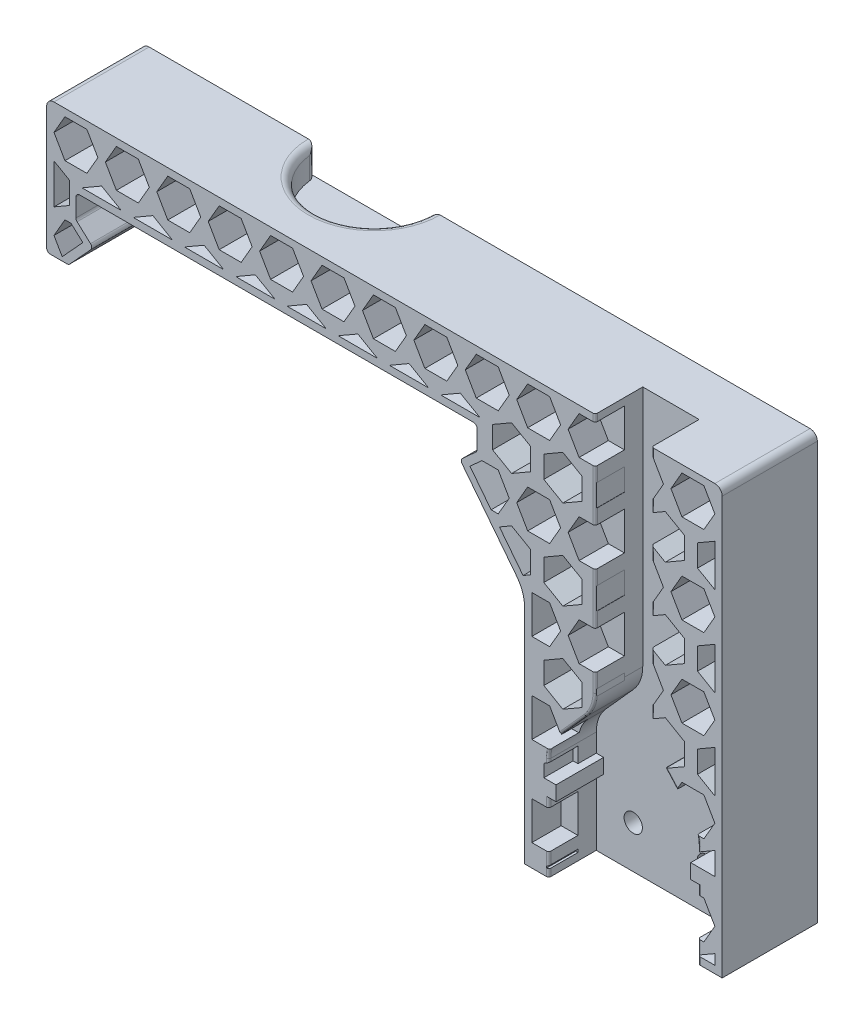
SolidWorks part; units mm, degrees
ref_plane "Front Plane" through (0, 0, 0) normal (0, 0, 1) x (1, 0, 0)
ref_plane "Top Plane" through (0, 0, 0) normal (0, 1, 0) x (1, 0, 0)
ref_plane "Right Plane" through (0, 0, 0) normal (1, 0, 0) x (0, 0, -1)
sketch "Sketch1" plane through (0, 0, 0) normal (0, 0, 1) x (1, 0, 0)
  line L0 (-72.9454, -38.2644) -> (107.2141, -38.2644) construction
  line L1 (-30.4, 19.7356) -> (59.88, 19.7356)
  line L2 (-31.4, 18.7356) -> (-31.4, 1.9656)
  line L3 (33.88, -38.2644) -> (60.88, -38.2644)
  line L4 (60.88, 18.7356) -> (60.88, -38.2644)
  line L5 (25.3801, 4.7612) -> (32.8222, -4.7779)
  line L6 (33.88, -38.2644) -> (33.88, -7.8535)
  line L7 (-66.2153, 1.4656) -> (103.3314, 1.4656) construction
  line L8 (-27.4, 34.7401) -> (-27.4, -56.6339) construction
  line L9 (-30.9, 1.4656) -> (-28.62, 1.4656)
  line L10 (-28.2514, 1.6278) -> (-25.3801, 4.7612)
  line L11 (-25.411, 5.4677) -> (-27.2378, 7.1416)
  line L12 (-40.4336, 7.2903) -> (-15.6218, 7.2903) construction
  line L13 (-40.4336, 10.4903) -> (107.2141, 10.4903) construction
  line L14 (-27.4, 7.5103) -> (-27.4, 9.9903)
  line L15 (0, 58.4136) -> (0, -42.5498) construction
  line L16 (27.4, 7.5103) -> (27.4, 9.9903)
  line L17 (25.411, 5.4677) -> (27.2378, 7.1416)
  line L20 (-26.9, 10.4903) -> (26.9, 10.4903)
  arc A0 (-27.2378, 7.1416) -> (-27.4, 7.5103) centre (-26.9, 7.5103) cw
  arc A1 (-25.3801, 4.7612) -> (-25.411, 5.4677) centre (-25.7488, 5.099) ccw
  arc A2 (-28.2514, 1.6278) -> (-28.62, 1.4656) centre (-28.62, 1.9656) cw
  arc A3 (-30.9, 1.4656) -> (-31.4, 1.9656) centre (-30.9, 1.9656) cw
  arc A4 (27.2378, 7.1416) -> (27.4, 7.5103) centre (26.9, 7.5103) ccw
  arc A5 (25.3801, 4.7612) -> (25.411, 5.4677) centre (25.7488, 5.099) cw
  arc A6 (33.88, -7.8535) -> (32.8222, -4.7779) centre (28.88, -7.8535) ccw
  arc A7 (-30.4, 19.7356) -> (-31.4, 18.7356) centre (-30.4, 18.7356) ccw
  arc A8 (27.4, 9.9903) -> (26.9, 10.4903) centre (26.9, 9.9903) ccw
  arc A9 (-26.9, 10.4903) -> (-27.4, 9.9903) centre (-26.9, 9.9903) ccw
  arc A10 (60.88, 18.7356) -> (59.88, 19.7356) centre (59.88, 18.7356) ccw
  point P0 (0, 0)
  point P23 (-27.4, 7.2903)
  point P26 (-25.0423, 5.1299)
  point P29 (-28.4, 1.4656)
  point P49 (27.4, 10.4903)
  point P52 (-27.4, 10.4903)
  point P53 (-31.4, 19.7356)
  point P56 (60.88, 19.7356)
  dimension "D11" = 0.5
  dimension "D12" = 0.5
  dimension "D15" = 5
  dimension "D16" = 1
  dimension "D1" = 92.28
  dimension "D2" = 58
  dimension "D3" = 18.27
  dimension "D4" = 4
  dimension "D5" = 132.5
  dimension "D6" = 4.97
  dimension "D7" = 90
  dimension "D8" = 54.8
  dimension "D9" = 3.1978
  dimension "D10" = 3.2
  dimension "D13" = 27
  dimension "D14" = 142.04
extrude "Boss-Extrude1" add sketch "Sketch1" along normal mid plane 13
sketch "Sketch2" plane through (0, 19.7356, 0) normal (0, 1, 0) x (1, 0, 0)
  line L0 (0.35, 16.9298) -> (0.35, -17.4429) construction
  line L1 (-31.4, -6.5) -> (-31.4, 6.5) construction
  circle A0 centre (0.35, 6.5) radius 8
  dimension "D2" = 16
  dimension "D1" = 31.75
extrude "Cut-Extrude1" cut sketch "Sketch2" against normal blind 4
fillet "Fillet1" radius 1 3 edges at (-7.65, 17.7356, -6.5) (8.35, 17.7356, -6.5) (0.35, 19.7356, 1.5)
sketch "Sketch3" plane through (0, 0, 6.5) normal (0, 0, 1) x (1, 0, 0)
  line L0 (47.38, -46.7699) -> (47.38, 28.5423) construction
  line L1 (0, -32.4644) -> (121.6508, -32.4644) construction
  line L2 (0, -28.7644) -> (121.6508, -28.7644) construction
  line L3 (33.88, -7.8535) -> (33.88, -38.2644) construction
  line L4 (60.88, -38.2644) -> (60.88, 18.7356) construction
  line L5 (43.53, 19.7356) -> (43.53, -13.3516)
  line L6 (59.88, 19.7356) -> (-30.4, 19.7356) construction
  line L7 (51.23, 19.7356) -> (51.23, -13.3516)
  line L8 (37.18, -38.2644) -> (37.18, -24.2619)
  line L9 (33.88, -38.2644) -> (60.88, -38.2644) construction
  line L10 (57.58, -38.2644) -> (57.58, -24.2619)
  line L11 (52.5067, -16.6888) -> (56.3033, -20.9247)
  line L12 (42.2533, -16.6888) -> (38.4567, -20.9247)
  line L13 (53.48, -29.3335) -> (53.48, -36.8232) construction
  line L14 (50.98, -29.3335) -> (50.98, -36.8232) construction
  line L15 (43.48, -29.3335) -> (43.48, -36.8232) construction
  line L16 (37.18, -26.7644) -> (38.18, -26.7644)
  line L17 (57.58, -28.7644) -> (56.58, -28.7644)
  line L19 (57.58, -26.7644) -> (56.58, -26.7644)
  line L20 (56.58, -28.7644) -> (56.58, -26.7644)
  line L21 (38.18, -28.7644) -> (38.18, -26.7644)
  line L22 (37.18, -28.7644) -> (38.18, -28.7644)
  line L24 (37.18, -38.2644) -> (57.58, -38.2644)
  line L25 (43.53, 19.7356) -> (51.23, 19.7356)
  arc A0 (42.2533, -16.6888) -> (43.53, -13.3516) centre (38.53, -13.3516) ccw
  arc A1 (52.5067, -16.6888) -> (51.23, -13.3516) centre (56.23, -13.3516) cw
  arc A2 (57.58, -24.2619) -> (56.3033, -20.9247) centre (52.58, -24.2619) ccw
  arc A3 (37.18, -24.2619) -> (38.4567, -20.9247) centre (42.18, -24.2619) cw
  circle A4 centre (52.23, -32.4644) radius 1.25
  circle A5 centre (42.23, -32.4644) radius 1.25
  point P27 (51.23, -15.2644)
  line M20 (59.88, 19.7356) -> (-30.4, 19.7356)
  line M41 (33.88, -38.2644) -> (60.88, -38.2644)
  dimension "D6" = 5
  dimension "D7" = 5
  dimension "D10" = 2.5
  dimension "D12" = 2.5
  dimension "D1" = 7.7
  dimension "D2" = 35
  dimension "D3" = 138.13
  dimension "D4" = 138.13
  dimension "D5" = 20.4
  dimension "D8" = 5.8
  dimension "D9" = 9.5
  dimension "D11" = 4.1
  dimension "D13" = 7.5
  dimension "D14" = 1
  dimension "D15" = 2
extrude "Cut-Extrude2" cut sketch "Sketch3" against normal blind 6.5 contours A3 L8 L16 L21 L22 L10 L17 L20 L19 A2 L11 A1 L7 L5 A0 L12 A5 A4 M41 M20
sketch "Sketch4" plane through (0, 0, 6.5) normal (0, 0, 1) x (1, 0, 0)
  circle A0 centre (42.23, -32.4644) radius 1.25
  circle A1 centre (52.23, -32.4644) radius 1.25
extrude "Cut-Extrude3" cut sketch "Sketch4" against normal blind 10
fillet "Fillet2" radius 0.3 12 edges at (51.23, 3.192, 6.5) (51.5601, -15.1381, 6.5) (57.58, -25.5131, 6.5) (57.2499, -22.4753, 6.5) (37.18, -25.5131, 6.5) (37.5101, -22.4753, 6.5) (40.355, -18.8067, 6.5) (43.1999, -15.1381, 6.5) (37.18, -33.5144, 6.5) (57.58, -33.5144, 6.5) (54.405, -18.8067, 6.5) (43.53, 3.192, 6.5)
sketch "Sketch5" plane through (0, 0, 6.5) normal (0, 0, 1) x (1, 0, 0)
  line L0 (-31.4, 18.7356) -> (-31.4, 1.9656) construction
  line L1 (-25.9, 13.5394) -> (-24.4, 16.1375)
  line L2 (-24.4, 16.1375) -> (-25.9, 18.7356)
  line L3 (-25.9, 18.7356) -> (-28.9, 18.7356)
  line L4 (-28.9, 18.7356) -> (-30.4, 16.1375)
  line L5 (-30.4, 16.1375) -> (-28.9, 13.5394)
  line L6 (-28.9, 13.5394) -> (-25.9, 13.5394)
  line L7 (43.23, 19.7356) -> (-30.4, 19.7356) construction
  line L8 (-18.8767, 13.5394) -> (-17.3767, 16.1375)
  line L9 (-17.3767, 16.1375) -> (-18.8767, 18.7356)
  line L10 (-18.8767, 18.7356) -> (-21.8767, 18.7356)
  line L11 (-21.8767, 18.7356) -> (-23.3767, 16.1375)
  line L12 (-23.3767, 16.1375) -> (-21.8767, 13.5394)
  line L13 (-21.8767, 13.5394) -> (-18.8767, 13.5394)
  line L14 (-11.8533, 13.5394) -> (-10.3533, 16.1375)
  line L15 (-10.3533, 16.1375) -> (-11.8533, 18.7356)
  line L16 (-11.8533, 18.7356) -> (-14.8533, 18.7356)
  line L17 (-14.8533, 18.7356) -> (-16.3533, 16.1375)
  line L18 (-16.3533, 16.1375) -> (-14.8533, 13.5394)
  line L19 (-14.8533, 13.5394) -> (-11.8533, 13.5394)
  line L20 (-4.83, 13.5394) -> (-3.33, 16.1375)
  line L21 (-3.33, 16.1375) -> (-4.83, 18.7356)
  line L22 (-4.83, 18.7356) -> (-7.83, 18.7356)
  line L23 (-7.83, 18.7356) -> (-9.33, 16.1375)
  line L24 (-9.33, 16.1375) -> (-7.83, 13.5394)
  line L25 (-7.83, 13.5394) -> (-4.83, 13.5394)
  line L26 (2.1933, 13.5394) -> (3.6933, 16.1375)
  line L27 (3.6933, 16.1375) -> (2.1933, 18.7356)
  line L28 (2.1933, 18.7356) -> (-0.8067, 18.7356)
  line L29 (-0.8067, 18.7356) -> (-2.3067, 16.1375)
  line L30 (-2.3067, 16.1375) -> (-0.8067, 13.5394)
  line L31 (-0.8067, 13.5394) -> (2.1933, 13.5394)
  line L32 (9.2167, 13.5394) -> (10.7167, 16.1375)
  line L33 (10.7167, 16.1375) -> (9.2167, 18.7356)
  line L34 (9.2167, 18.7356) -> (6.2167, 18.7356)
  line L35 (6.2167, 18.7356) -> (4.7167, 16.1375)
  line L36 (4.7167, 16.1375) -> (6.2167, 13.5394)
  line L37 (6.2167, 13.5394) -> (9.2167, 13.5394)
  line L38 (16.24, 13.5394) -> (17.74, 16.1375)
  line L39 (17.74, 16.1375) -> (16.24, 18.7356)
  line L40 (16.24, 18.7356) -> (13.24, 18.7356)
  line L41 (13.24, 18.7356) -> (11.74, 16.1375)
  line L42 (11.74, 16.1375) -> (13.24, 13.5394)
  line L43 (13.24, 13.5394) -> (16.24, 13.5394)
  line L44 (23.2633, 13.5394) -> (24.7633, 16.1375)
  line L45 (24.7633, 16.1375) -> (23.2633, 18.7356)
  line L46 (23.2633, 18.7356) -> (20.2633, 18.7356)
  line L47 (20.2633, 18.7356) -> (18.7633, 16.1375)
  line L48 (18.7633, 16.1375) -> (20.2633, 13.5394)
  line L49 (20.2633, 13.5394) -> (23.2633, 13.5394)
  line L50 (30.2867, 13.5394) -> (31.7867, 16.1375)
  line L51 (31.7867, 16.1375) -> (30.2867, 18.7356)
  line L52 (30.2867, 18.7356) -> (27.2867, 18.7356)
  line L53 (27.2867, 18.7356) -> (25.7867, 16.1375)
  line L54 (25.7867, 16.1375) -> (27.2867, 13.5394)
  line L55 (27.2867, 13.5394) -> (30.2867, 13.5394)
  line L56 (37.31, 13.5394) -> (38.81, 16.1375)
  line L57 (38.81, 16.1375) -> (37.31, 18.7356)
  line L58 (37.31, 18.7356) -> (34.31, 18.7356)
  line L59 (34.31, 18.7356) -> (32.81, 16.1375)
  line L60 (32.81, 16.1375) -> (34.31, 13.5394)
  line L61 (34.31, 13.5394) -> (37.31, 13.5394)
  line L62 (44.3333, 13.5394) -> (45.8333, 16.1375)
  line L63 (45.8333, 16.1375) -> (44.3333, 18.7356)
  line L64 (44.3333, 18.7356) -> (41.3333, 18.7356)
  line L65 (41.3333, 18.7356) -> (39.8333, 16.1375)
  line L66 (39.8333, 16.1375) -> (41.3333, 13.5394)
  line L67 (41.3333, 13.5394) -> (44.3333, 13.5394)
  line L68 (51.3567, 13.5394) -> (52.8567, 16.1375)
  line L69 (52.8567, 16.1375) -> (51.3567, 18.7356)
  line L70 (51.3567, 18.7356) -> (48.3567, 18.7356)
  line L71 (48.3567, 18.7356) -> (46.8567, 16.1375)
  line L72 (46.8567, 16.1375) -> (48.3567, 13.5394)
  line L73 (48.3567, 13.5394) -> (51.3567, 13.5394)
  line L74 (58.38, 13.5394) -> (59.88, 16.1375)
  line L75 (59.88, 16.1375) -> (58.38, 18.7356)
  line L76 (58.38, 18.7356) -> (55.38, 18.7356)
  line L77 (55.38, 18.7356) -> (53.88, 16.1375)
  line L78 (53.88, 16.1375) -> (55.38, 13.5394)
  line L79 (55.38, 13.5394) -> (58.38, 13.5394)
  line L80 (60.88, -38.2644) -> (60.88, 18.7356) construction
  line L81 (-23.8883, 20.8611) -> (-23.8883, 11.4903) construction
  line L89 (-21.2903, 11.4903) -> (-21.2903, 11.5394)
  line L90 (-21.2903, 11.5394) -> (-23.8883, 13.0394)
  line L91 (-23.8883, 13.0394) -> (-26.4864, 11.5394)
  line L92 (-26.4864, 11.5394) -> (-26.4864, 11.4903)
  line L95 (-14.2903, 11.4903) -> (-14.2903, 11.5394)
  line L96 (-14.2903, 11.5394) -> (-16.8883, 13.0394)
  line L97 (-16.8883, 13.0394) -> (-19.4864, 11.5394)
  line L98 (-19.4864, 11.5394) -> (-19.4864, 11.4903)
  line L101 (-7.2903, 11.4903) -> (-7.2903, 11.5394)
  line L102 (-7.2903, 11.5394) -> (-9.8883, 13.0394)
  line L103 (-9.8883, 13.0394) -> (-12.4864, 11.5394)
  line L104 (-12.4864, 11.5394) -> (-12.4864, 11.4903)
  line L107 (-0.2903, 11.4903) -> (-0.2903, 11.5394)
  line L108 (-0.2903, 11.5394) -> (-2.8883, 13.0394)
  line L109 (-2.8883, 13.0394) -> (-5.4864, 11.5394)
  line L110 (-5.4864, 11.5394) -> (-5.4864, 11.4903)
  line L113 (6.7097, 11.4903) -> (6.7097, 11.5394)
  line L114 (6.7097, 11.5394) -> (4.1117, 13.0394)
  line L115 (4.1117, 13.0394) -> (1.5136, 11.5394)
  line L116 (1.5136, 11.5394) -> (1.5136, 11.4903)
  line L119 (13.7097, 11.4903) -> (13.7097, 11.5394)
  line L120 (13.7097, 11.5394) -> (11.1117, 13.0394)
  line L121 (11.1117, 13.0394) -> (8.5136, 11.5394)
  line L122 (8.5136, 11.5394) -> (8.5136, 11.4903)
  line L125 (20.7097, 11.4903) -> (20.7097, 11.5394)
  line L126 (20.7097, 11.5394) -> (18.1117, 13.0394)
  line L127 (18.1117, 13.0394) -> (15.5136, 11.5394)
  line L128 (15.5136, 11.5394) -> (15.5136, 11.4903)
  line L131 (27.7097, 11.4903) -> (27.7097, 11.5394)
  line L132 (27.7097, 11.5394) -> (25.1117, 13.0394)
  line L133 (25.1117, 13.0394) -> (22.5136, 11.5394)
  line L134 (22.5136, 11.5394) -> (22.5136, 11.4903)
  line L142 (39.1117, 7.0394) -> (41.7097, 8.5394)
  line L143 (41.7097, 8.5394) -> (41.7097, 11.5394)
  line L144 (41.7097, 11.5394) -> (39.1117, 13.0394)
  line L145 (39.1117, 13.0394) -> (36.5136, 11.5394)
  line L146 (36.5136, 11.5394) -> (36.5136, 8.5394)
  line L147 (36.5136, 8.5394) -> (39.1117, 7.0394)
  line L148 (46.1117, 7.0394) -> (48.7097, 8.5394)
  line L149 (48.7097, 8.5394) -> (48.7097, 11.5394)
  line L150 (48.7097, 11.5394) -> (46.1117, 13.0394)
  line L151 (46.1117, 13.0394) -> (43.5136, 11.5394)
  line L152 (43.5136, 11.5394) -> (43.5136, 8.5394)
  line L153 (43.5136, 8.5394) -> (46.1117, 7.0394)
  line L154 (53.1117, 7.0394) -> (55.7097, 8.5394)
  line L155 (55.7097, 8.5394) -> (55.7097, 11.5394)
  line L156 (55.7097, 11.5394) -> (53.1117, 13.0394)
  line L157 (53.1117, 13.0394) -> (50.5136, 11.5394)
  line L158 (50.5136, 11.5394) -> (50.5136, 8.5394)
  line L159 (50.5136, 8.5394) -> (53.1117, 7.0394)
  line L163 (59.88, 12.9057) -> (57.5136, 11.5394)
  line L164 (57.5136, 11.5394) -> (57.5136, 8.5394)
  line L165 (57.5136, 8.5394) -> (59.88, 7.1732)
  line L166 (-30.4, 7.3214) -> (-28.2903, 8.5394)
  line L167 (-28.2903, 8.5394) -> (-28.2903, 11.5394)
  line L168 (-28.2903, 11.5394) -> (-30.4, 12.7575)
  line L172 (-30.4, 25.6172) -> (-30.4, -2.2166) construction
  line L173 (59.88, 25.6172) -> (59.88, -37.2644) construction
  line L174 (34.88, -39.7832) -> (34.88, 44.6202) construction
  line L175 (33.88, -7.8535) -> (33.88, -38.2644) construction
  line L176 (-30.4, 12.7575) -> (-30.4, 7.3214)
  line L177 (-27.5969, 11.4903) -> (59.88, 11.4903) construction
  line L178 (-26.9, 10.4903) -> (26.9, 10.4903) construction
  line L179 (-30.8883, 13.0394) -> (-33.4864, 11.5394) [skipped]
  line L180 (-33.4864, 11.5394) -> (-33.4864, 8.5394) [skipped]
  line L181 (32.1117, 7.0394) -> (34.7097, 8.5394)
  line L182 (-26.4864, 11.4903) -> (-21.2903, 11.4903)
  line L183 (-19.4864, 11.4903) -> (-14.2903, 11.4903)
  line L184 (-12.4864, 11.4903) -> (-7.2903, 11.4903)
  line L185 (-5.4864, 11.4903) -> (-0.2903, 11.4903)
  line L186 (1.5136, 11.4903) -> (6.7097, 11.4903)
  line L187 (8.5136, 11.4903) -> (13.7097, 11.4903)
  line L188 (15.5136, 11.4903) -> (20.7097, 11.4903)
  line L189 (22.5136, 11.4903) -> (27.7097, 11.4903)
  line L190 (59.88, 12.9057) -> (59.88, 7.1732)
  line L191 (-23.8883, 7.4414) -> (-23.8883, 3.5852) construction
  line L192 (34.7097, 8.5394) -> (34.7097, 11.5394)
  line L193 (62.7097, 11.5394) -> (60.1117, 13.0394) [skipped]
  line L194 (34.7097, 11.5394) -> (32.1117, 13.0394)
  line L195 (62.7097, 11.4903) -> (62.7097, 11.5394) [skipped]
  line L196 (32.1117, 13.0394) -> (29.5136, 11.5394)
  line L197 (29.5136, 11.5394) -> (29.5136, 8.5394)
  line L198 (29.5136, 8.5394) -> (32.1117, 7.0394)
  line L199 (-34.5969, 11.4903) -> (52.88, 11.4903) construction
  line L200 (-25.1874, 7.7894) -> (-23.8883, 7.0394) [skipped]
  line L201 (-23.8883, 7.0394) -> (-21.2903, 8.5394) [skipped]
  line L202 (29.5136, 11.5394) -> (29.5136, 11.4903) [skipped]
  line L203 (32.1117, 13.0394) -> (29.5136, 11.5394) [skipped]
  line L204 (34.7097, 11.4903) -> (34.7097, 11.5394) [skipped]
  line L205 (34.7097, 11.5394) -> (32.1117, 13.0394) [skipped]
  line L208 (-28.0608, 6.5394) -> (-28.9, 6.5394)
  line L209 (-28.9, 6.5394) -> (-30.4, 3.9414)
  line L210 (-30.4, 3.9414) -> (-29.2743, 1.9916)
  line L254 (30.2867, 1.3433) -> (31.7867, 3.9414)
  line L255 (31.7867, 3.9414) -> (30.2867, 6.5394)
  line L256 (30.2867, 6.5394) -> (28.0608, 6.5394)
  line L257 (26.4252, 5.0473) -> (26.4171, 5.0332)
  line L259 (29.315, 1.3433) -> (30.2867, 1.3433)
  line L260 (37.31, 1.3433) -> (38.81, 3.9414)
  line L261 (38.81, 3.9414) -> (37.31, 6.5394)
  line L262 (37.31, 6.5394) -> (34.31, 6.5394)
  line L263 (34.31, 6.5394) -> (32.81, 3.9414)
  line L264 (32.81, 3.9414) -> (34.31, 1.3433)
  line L265 (34.31, 1.3433) -> (37.31, 1.3433)
  line L266 (44.3333, 1.3433) -> (45.8333, 3.9414)
  line L267 (45.8333, 3.9414) -> (44.3333, 6.5394)
  line L268 (44.3333, 6.5394) -> (41.3333, 6.5394)
  line L269 (41.3333, 6.5394) -> (39.8333, 3.9414)
  line L270 (39.8333, 3.9414) -> (41.3333, 1.3433)
  line L271 (41.3333, 1.3433) -> (44.3333, 1.3433)
  line L272 (51.3567, 1.3433) -> (52.8567, 3.9414)
  line L273 (52.8567, 3.9414) -> (51.3567, 6.5394)
  line L274 (51.3567, 6.5394) -> (48.3567, 6.5394)
  line L275 (48.3567, 6.5394) -> (46.8567, 3.9414)
  line L276 (46.8567, 3.9414) -> (48.3567, 1.3433)
  line L277 (48.3567, 1.3433) -> (51.3567, 1.3433)
  line L278 (58.38, 1.3433) -> (59.88, 3.9414)
  line L279 (59.88, 3.9414) -> (58.38, 6.5394)
  line L280 (58.38, 6.5394) -> (55.38, 6.5394)
  line L281 (55.38, 6.5394) -> (53.88, 3.9414)
  line L282 (53.88, 3.9414) -> (55.38, 1.3433)
  line L283 (55.38, 1.3433) -> (58.38, 1.3433)
  line L284 (-29.9967, 1.2033) -> (-24.7531, 6.9257) construction
  line L285 (-28.2514, 1.6278) -> (-25.3801, 4.7612) construction
  line L286 (-23.2608, 2.1411) -> (-28.8272, 7.2417) construction
  line L287 (-25.411, 5.4677) -> (-27.2378, 7.1416) construction
  line L288 (-28.0608, 6.5394) -> (-26.4552, 5.0682)
  line L289 (-26.4552, 5.0682) -> (-29.2743, 1.9916)
  line L290 (36.4614, -7.8169) -> (25.0514, 6.8083) construction
  line L291 (25.3801, 4.7612) -> (32.8222, -4.7779) construction
  line L292 (-28.9, 1.3433) -> (-25.9, 1.3433) [skipped]
  line L293 (-24.6856, 3.4467) -> (-24.4, 3.9414) [skipped]
  line L294 (-25.5935, 6.0085) -> (-25.9, 6.5394) [skipped]
  line L295 (-21.8767, 1.3433) -> (-18.8767, 1.3433) [skipped]
  line L296 (-23.3767, 3.9414) -> (-21.8767, 1.3433) [skipped]
  line L297 (-21.8767, 6.5394) -> (-23.3767, 3.9414) [skipped]
  line L298 (-18.8767, 6.5394) -> (-21.8767, 6.5394) [skipped]
  line L299 (-17.3767, 3.9414) -> (-18.8767, 6.5394) [skipped]
  line L300 (-18.8767, 1.3433) -> (-17.3767, 3.9414) [skipped]
  line L301 (-11.8533, 1.3433) -> (-10.3533, 3.9414) [skipped]
  line L302 (-14.8533, 1.3433) -> (-11.8533, 1.3433) [skipped]
  line L303 (-10.3533, 3.9414) -> (-11.8533, 6.5394) [skipped]
  line L304 (-14.8533, 6.5394) -> (-16.3533, 3.9414) [skipped]
  line L305 (-11.8533, 6.5394) -> (-14.8533, 6.5394) [skipped]
  line L306 (-16.3533, 3.9414) -> (-14.8533, 1.3433) [skipped]
  line L307 (-7.83, 1.3433) -> (-4.83, 1.3433) [skipped]
  line L308 (-4.83, 1.3433) -> (-3.33, 3.9414) [skipped]
  line L309 (-3.33, 3.9414) -> (-4.83, 6.5394) [skipped]
  line L310 (-4.83, 6.5394) -> (-7.83, 6.5394) [skipped]
  line L311 (-7.83, 6.5394) -> (-9.33, 3.9414) [skipped]
  line L312 (-9.33, 3.9414) -> (-7.83, 1.3433) [skipped]
  line L313 (20.2633, 1.3433) -> (23.2633, 1.3433) [skipped]
  line L314 (23.2633, 6.5394) -> (20.2633, 6.5394) [skipped]
  line L315 (20.2633, 6.5394) -> (18.7633, 3.9414) [skipped]
  line L316 (18.7633, 3.9414) -> (20.2633, 1.3433) [skipped]
  line L317 (16.24, 1.3433) -> (17.74, 3.9414) [skipped]
  line L318 (13.24, 1.3433) -> (16.24, 1.3433) [skipped]
  line L319 (11.74, 3.9414) -> (13.24, 1.3433) [skipped]
  line L320 (13.24, 6.5394) -> (11.74, 3.9414) [skipped]
  line L321 (16.24, 6.5394) -> (13.24, 6.5394) [skipped]
  line L322 (17.74, 3.9414) -> (16.24, 6.5394) [skipped]
  line L323 (9.2167, 1.3433) -> (10.7167, 3.9414) [skipped]
  line L324 (10.7167, 3.9414) -> (9.2167, 6.5394) [skipped]
  line L325 (4.7167, 3.9414) -> (6.2167, 1.3433) [skipped]
  line L326 (6.2167, 1.3433) -> (9.2167, 1.3433) [skipped]
  line L327 (6.2167, 6.5394) -> (4.7167, 3.9414) [skipped]
  line L328 (9.2167, 6.5394) -> (6.2167, 6.5394) [skipped]
  line L329 (2.1933, 1.3433) -> (3.6933, 3.9414) [skipped]
  line L330 (-0.8067, 1.3433) -> (2.1933, 1.3433) [skipped]
  line L331 (-2.3067, 3.9414) -> (-0.8067, 1.3433) [skipped]
  line L332 (-0.8067, 6.5394) -> (-2.3067, 3.9414) [skipped]
  line L333 (2.1933, 6.5394) -> (-0.8067, 6.5394) [skipped]
  line L334 (3.6933, 3.9414) -> (2.1933, 6.5394) [skipped]
  line L335 (23.2633, 1.3433) -> (24.7633, 3.9414) [skipped]
  line L336 (24.7633, 3.9414) -> (23.2633, 6.5394) [skipped]
  line L337 (26.4171, 5.0332) -> (28.9645, 7.3675) construction
  line L338 (27.2378, 7.1416) -> (25.411, 5.4677) construction
  line L339 (29.315, 1.3433) -> (26.4252, 5.0473)
  line L340 (26.4252, 5.0473) -> (28.0608, 6.5394)
  line L341 (33.6797, -4.2514) -> (34.7097, -3.6567)
  line L342 (34.7097, -3.6567) -> (34.7097, -0.6567)
  line L343 (25.7867, 3.9414) -> (27.2867, 1.3433) [skipped]
  line L344 (34.7097, -0.6567) -> (32.1117, 0.8433)
  line L345 (32.1117, 0.8433) -> (30.4524, -0.1147)
  line L348 (46.1117, -5.1567) -> (48.7097, -3.6567)
  line L349 (48.7097, -3.6567) -> (48.7097, -0.6567)
  line L350 (48.7097, -0.6567) -> (46.1117, 0.8433)
  line L351 (46.1117, 0.8433) -> (43.5136, -0.6567)
  line L352 (43.5136, -0.6567) -> (43.5136, -3.6567)
  line L353 (43.5136, -3.6567) -> (46.1117, -5.1567)
  line L354 (53.1117, -5.1567) -> (55.7097, -3.6567)
  line L355 (55.7097, -3.6567) -> (55.7097, -0.6567)
  line L356 (55.7097, -0.6567) -> (53.1117, 0.8433)
  line L357 (53.1117, 0.8433) -> (50.5136, -0.6567)
  line L358 (50.5136, -0.6567) -> (50.5136, -3.6567)
  line L359 (50.5136, -3.6567) -> (53.1117, -5.1567)
  line L360 (57.5136, -0.6567) -> (57.5136, -3.6567)
  line L361 (57.5136, -3.6567) -> (59.88, -5.023)
  line L362 (59.88, 0.7095) -> (59.88, -5.023)
  line L363 (59.88, 0.7095) -> (57.5136, -0.6567)
  line L364 (39.1117, -5.1567) -> (41.7097, -3.6567)
  line L365 (41.7097, -3.6567) -> (41.7097, -0.6567)
  line L366 (41.7097, -0.6567) -> (39.1117, 0.8433)
  line L367 (39.1117, 0.8433) -> (36.5136, -0.6567)
  line L368 (36.5136, -0.6567) -> (36.5136, -3.6567)
  line L369 (36.5136, -3.6567) -> (39.1117, -5.1567)
  line L370 (43.23, -13.3516) -> (43.23, 19.7356) construction
  line L371 (30.4524, -0.1147) -> (33.6797, -4.2514)
  line L372 (37.31, -10.8529) -> (38.81, -8.2548)
  line L373 (38.81, -8.2548) -> (37.31, -5.6567)
  line L374 (29.5136, -0.6567) -> (29.5136, -3.6567) [skipped]
  line L375 (29.5136, -3.6567) -> (32.1117, -5.1567) [skipped]
  line L376 (37.31, -5.6567) -> (34.88, -5.6567)
  line L379 (34.88, -10.8529) -> (37.31, -10.8529)
  line L380 (44.3333, -10.8529) -> (45.8333, -8.2548)
  line L381 (45.8333, -8.2548) -> (44.3333, -5.6567)
  line L382 (44.3333, -5.6567) -> (41.3333, -5.6567)
  line L383 (41.3333, -5.6567) -> (39.8333, -8.2548)
  line L384 (39.8333, -8.2548) -> (41.3333, -10.8529)
  line L385 (41.3333, -10.8529) -> (44.3333, -10.8529)
  line L386 (51.3567, -10.8529) -> (52.8567, -8.2548)
  line L387 (52.8567, -8.2548) -> (51.3567, -5.6567)
  line L388 (51.3567, -5.6567) -> (48.3567, -5.6567)
  line L389 (48.3567, -5.6567) -> (46.8567, -8.2548)
  line L390 (46.8567, -8.2548) -> (48.3567, -10.8529)
  line L391 (48.3567, -10.8529) -> (51.3567, -10.8529)
  line L392 (58.38, -10.8529) -> (59.88, -8.2548)
  line L393 (59.88, -8.2548) -> (58.38, -5.6567)
  line L394 (58.38, -5.6567) -> (55.38, -5.6567)
  line L395 (55.38, -5.6567) -> (53.88, -8.2548)
  line L396 (53.88, -8.2548) -> (55.38, -10.8529)
  line L397 (55.38, -10.8529) -> (58.38, -10.8529)
  line L398 (34.88, -5.6567) -> (34.88, -10.8529)
  line L401 (32.81, -8.2548) -> (34.31, -10.8529) [skipped]
  line L402 (34.31, -5.6567) -> (32.81, -8.2548) [skipped]
  line L407 (39.1117, -17.3529) -> (41.7097, -15.8529)
  line L408 (41.7097, -15.8529) -> (41.7097, -12.8529)
  line L409 (41.7097, -12.8529) -> (39.1117, -11.3529)
  line L410 (39.1117, -11.3529) -> (36.5136, -12.8529)
  line L411 (36.5136, -12.8529) -> (36.5136, -15.8529)
  line L412 (36.5136, -15.8529) -> (39.1117, -17.3529)
  line L413 (46.1117, -17.3529) -> (48.7097, -15.8529)
  line L414 (48.7097, -15.8529) -> (48.7097, -12.8529)
  line L415 (48.7097, -12.8529) -> (46.1117, -11.3529)
  line L416 (46.1117, -11.3529) -> (43.5136, -12.8529)
  line L417 (43.5136, -12.8529) -> (43.5136, -15.8529)
  line L418 (43.5136, -15.8529) -> (46.1117, -17.3529)
  line L419 (53.1117, -17.3529) -> (55.7097, -15.8529)
  line L420 (55.7097, -15.8529) -> (55.7097, -12.8529)
  line L421 (55.7097, -12.8529) -> (53.1117, -11.3529)
  line L422 (53.1117, -11.3529) -> (50.5136, -12.8529)
  line L423 (50.5136, -12.8529) -> (50.5136, -15.8529)
  line L424 (50.5136, -15.8529) -> (53.1117, -17.3529)
  line L425 (57.5136, -12.8529) -> (57.5136, -15.8529)
  line L426 (57.5136, -15.8529) -> (59.88, -17.2191)
  line L427 (59.88, -11.4866) -> (59.88, -17.2191)
  line L428 (59.88, -11.4866) -> (57.5136, -12.8529)
  line L429 (32.1117, -11.3529) -> (29.5136, -12.8529) [skipped]
  line L430 (29.5136, -12.8529) -> (29.5136, -15.8529) [skipped]
  line L431 (29.5136, -15.8529) -> (32.1117, -17.3529) [skipped]
  line L432 (32.1117, -17.3529) -> (34.7097, -15.8529) [skipped]
  line L433 (34.7097, -15.8529) -> (34.7097, -12.8529) [skipped]
  line L434 (34.7097, -12.8529) -> (32.1117, -11.3529) [skipped]
  line L435 (38.81, -20.4509) -> (37.31, -17.8529)
  line L436 (37.31, -17.8529) -> (34.88, -17.8529)
  line L437 (34.88, -17.8529) -> (34.88, -23.049)
  line L438 (34.88, -23.049) -> (37.31, -23.049)
  line L439 (37.31, -23.049) -> (38.81, -20.4509)
  line L440 (44.3333, -23.049) -> (45.8333, -20.4509)
  line L441 (45.8333, -20.4509) -> (44.3333, -17.8529)
  line L442 (44.3333, -17.8529) -> (41.3333, -17.8529)
  line L443 (41.3333, -17.8529) -> (39.8333, -20.4509)
  line L444 (39.8333, -20.4509) -> (41.3333, -23.049)
  line L445 (41.3333, -23.049) -> (44.3333, -23.049)
  line L446 (51.3567, -23.049) -> (52.8567, -20.4509)
  line L447 (52.8567, -20.4509) -> (51.3567, -17.8529)
  line L448 (51.3567, -17.8529) -> (48.3567, -17.8529)
  line L449 (48.3567, -17.8529) -> (46.8567, -20.4509)
  line L450 (46.8567, -20.4509) -> (48.3567, -23.049)
  line L451 (48.3567, -23.049) -> (51.3567, -23.049)
  line L452 (58.38, -23.049) -> (59.88, -20.4509)
  line L453 (59.88, -20.4509) -> (58.38, -17.8529)
  line L454 (58.38, -17.8529) -> (55.38, -17.8529)
  line L455 (55.38, -17.8529) -> (53.88, -20.4509)
  line L456 (53.88, -20.4509) -> (55.38, -23.049)
  line L457 (55.38, -23.049) -> (58.38, -23.049)
  line L458 (39.1117, -29.549) -> (41.7097, -28.049)
  line L459 (41.7097, -28.049) -> (41.7097, -25.049)
  line L460 (41.7097, -25.049) -> (39.1117, -23.549)
  line L461 (39.1117, -23.549) -> (36.5136, -25.049)
  line L462 (36.5136, -25.049) -> (36.5136, -28.049)
  line L463 (36.5136, -28.049) -> (39.1117, -29.549)
  line L464 (46.1117, -29.549) -> (48.7097, -28.049)
  line L465 (48.7097, -28.049) -> (48.7097, -25.049)
  line L466 (48.7097, -25.049) -> (46.1117, -23.549)
  line L467 (46.1117, -23.549) -> (43.5136, -25.049)
  line L468 (43.5136, -25.049) -> (43.5136, -28.049)
  line L469 (43.5136, -28.049) -> (46.1117, -29.549)
  line L470 (53.1117, -29.549) -> (55.7097, -28.049)
  line L471 (55.7097, -28.049) -> (55.7097, -25.049)
  line L472 (55.7097, -25.049) -> (53.1117, -23.549)
  line L473 (53.1117, -23.549) -> (50.5136, -25.049)
  line L474 (50.5136, -25.049) -> (50.5136, -28.049)
  line L475 (50.5136, -28.049) -> (53.1117, -29.549)
  line L476 (57.5136, -25.049) -> (57.5136, -28.049)
  line L477 (57.5136, -28.049) -> (59.88, -29.4153)
  line L478 (59.88, -23.6828) -> (59.88, -29.4153)
  line L479 (59.88, -23.6828) -> (57.5136, -25.049)
  line L480 (38.81, -32.6471) -> (37.31, -30.049)
  line L481 (37.31, -30.049) -> (34.88, -30.049)
  line L482 (34.88, -30.049) -> (34.88, -35.2452)
  line L483 (34.88, -35.2452) -> (37.31, -35.2452)
  line L484 (37.31, -35.2452) -> (38.81, -32.6471)
  line L485 (44.3333, -35.2452) -> (45.8333, -32.6471)
  line L486 (45.8333, -32.6471) -> (44.3333, -30.049)
  line L487 (44.3333, -30.049) -> (41.3333, -30.049)
  line L488 (41.3333, -30.049) -> (39.8333, -32.6471)
  line L489 (39.8333, -32.6471) -> (41.3333, -35.2452)
  line L490 (41.3333, -35.2452) -> (44.3333, -35.2452)
  line L491 (51.3567, -35.2452) -> (52.8567, -32.6471)
  line L492 (52.8567, -32.6471) -> (51.3567, -30.049)
  line L493 (51.3567, -30.049) -> (48.3567, -30.049)
  line L494 (48.3567, -30.049) -> (46.8567, -32.6471)
  line L495 (46.8567, -32.6471) -> (48.3567, -35.2452)
  line L496 (48.3567, -35.2452) -> (51.3567, -35.2452)
  line L497 (58.38, -35.2452) -> (59.88, -32.6471)
  line L498 (59.88, -32.6471) -> (58.38, -30.049)
  line L499 (58.38, -30.049) -> (55.38, -30.049)
  line L500 (55.38, -30.049) -> (53.88, -32.6471)
  line L501 (53.88, -32.6471) -> (55.38, -35.2452)
  line L502 (55.38, -35.2452) -> (58.38, -35.2452)
  line L504 (41.7097, -37.2644) -> (41.7097, -37.2452)
  line L505 (41.7097, -37.2452) -> (39.1117, -35.7452)
  line L506 (39.1117, -35.7452) -> (36.5136, -37.2452)
  line L507 (36.5136, -37.2452) -> (36.5136, -37.2644)
  line L510 (48.7097, -37.2644) -> (48.7097, -37.2452)
  line L511 (48.7097, -37.2452) -> (46.1117, -35.7452)
  line L512 (46.1117, -35.7452) -> (43.5136, -37.2452)
  line L513 (43.5136, -37.2452) -> (43.5136, -37.2644)
  line L516 (55.7097, -37.2644) -> (55.7097, -37.2452)
  line L517 (55.7097, -37.2452) -> (53.1117, -35.7452)
  line L518 (53.1117, -35.7452) -> (50.5136, -37.2452)
  line L519 (50.5136, -37.2452) -> (50.5136, -37.2644)
  line L521 (57.5136, -37.2452) -> (57.5136, -37.2644)
  line L523 (59.88, -35.8789) -> (59.88, -37.2644)
  line L524 (59.88, -35.8789) -> (57.5136, -37.2452)
  line L525 (33.1213, -37.2644) -> (48.7097, -37.2644) construction
  line L526 (57.88, -38.2644) -> (60.88, -38.2644) construction
  line L527 (36.5136, -37.2644) -> (41.7097, -37.2644)
  line L528 (43.5136, -37.2644) -> (48.7097, -37.2644)
  line L529 (50.5136, -37.2644) -> (55.7097, -37.2644) construction
  line L530 (36.5136, -40.2452) -> (39.1117, -41.7452) [skipped]
  line L531 (39.1117, -41.7452) -> (41.7097, -40.2452) [skipped]
  line L532 (43.5136, -40.2452) -> (46.1117, -41.7452) [skipped]
  line L533 (46.1117, -41.7452) -> (48.7097, -40.2452) [skipped]
  line L534 (50.5136, -37.2644) -> (55.7097, -37.2644)
  line L535 (50.5136, -40.2452) -> (53.1117, -41.7452) [skipped]
  line L536 (53.1117, -41.7452) -> (55.7097, -40.2452) [skipped]
  line L537 (57.5136, -40.2452) -> (59.88, -41.6114) [skipped]
  line L538 (57.5136, -37.2644) -> (65.125, -37.2644) construction
  line L539 (57.5136, -37.2644) -> (59.88, -37.2644)
  line L540 (59.88, -41.6114) -> (59.88, -46.9443) construction
  circle A0 centre (-27.4, 16.1375) radius 2.5981 construction
  arc A1 (-21.7331, 11.4903) -> (-26.0436, 11.4903) centre (-23.8883, 10.0394) ccw construction
  point P135 (26.3244, 6.3046)
  line M162 (36.88, -38.2644) -> (36.88, -28.7644)
  line M163 (36.88, -28.7644) -> (38.18, -28.7644)
  line M164 (38.18, -28.7644) -> (38.18, -26.7644)
  line M165 (38.18, -26.7644) -> (36.88, -26.7644)
  line M166 (36.88, -26.7644) -> (36.88, -24.2619)
  arc M167 (36.88, -24.2619) -> (38.2333, -20.7244) centre (42.18, -24.2619) cw
  line M168 (38.2333, -20.7244) -> (42.0299, -16.4886)
  line M170 (43.23, -13.3516) -> (43.23, 19.7356)
  dimension "D19" = 13.915
  dimension "D1" = 1
  dimension "D2" = 1
  dimension "D3" = 3
  dimension "D5" = 1
  dimension "D6" = 2
  dimension "D7" = 0.5
  dimension "D10" = 1
  dimension "D11" = 1
  dimension "D13" = 0.5
  dimension "D14" = 1
  dimension "D15" = 1
  dimension "D16" = 1
  dimension "D17" = 1
  dimension "D20" = 0.5
  dimension "D21" = 2
  dimension "D22" = 0.5
  dimension "D23" = 2
  dimension "D24" = 0.5
  dimension "D26" = 0.5
  dimension "D28" = 0.5
  dimension "D30" = 0.5
  dimension "D32" = 0.5
  dimension "D33" = 1
  dimension "D4" = 13
  dimension "D8" = 13
  dimension "D9" = 2
  dimension "D12" = 2
  dimension "D18" = 2
  dimension "D25" = 2
  dimension "D27" = 2
  dimension "D29" = 2
  dimension "D31" = 2
extrude "Cut-Extrude4" cut sketch "Sketch5" against normal blind 4 contours L5 L6 L1 L2 L3 L4 | L12 L13 L8 L9 L10 L11 | L168 L176 L166 L167 | L289 L288 L208 L209 L210 | L92 L182 L89 L90 L91 | L98 L183 L95 L96 L97 | L18 L19 L14 L15 L16 L17 | L104 L184 L101 L102 L103 | L24 L25 L20 L21 L22 L23 | L110 L185 L107 L108 L109 | L116 L186 L113 L114 L115 | L122 L187 L119 L120 L121 | L128 L188 L125 L126 L127 | L134 L189 L131 L132 L133 | L54 L55 L50 L51 L52 L53 | L48 L49 L44 L45 L46 L47 | L42 L43 L38 L39 L40 L41 | L36 L37 L32 L33 L34 L35 | L30 L31 L26 L27 L28 L29 | L60 L61 L56 L57 L58 L59 | L197 L198 L181 L192 L194 L196 | L146 L147 L142 L143 L144 L145 | L66 L67 L64 L65 M170 | L152 L153 L148 L149 L150 L151 | L72 L73 L68 L69 L70 L71 | L158 L159 L154 L155 L156 L157 | L78 L79 L74 L75 L76 L77 | L67 L62 L63 L64 M170 | L190 L163 L164 L165 | L282 L283 L278 L279 L280 L281 | L276 L277 L272 L273 L274 L275 | L270 L271 L268 L269 M170 | L264 L265 L260 L261 L262 L263 | L340 L339 L259 L254 L255 L256 | L271 L266 L267 L268 M170 | L345 L371 L341 L342 L344 | L368 L369 L364 L365 L366 L367 | L352 L353 L348 L349 L350 L351 | L358 L359 L354 L355 L356 L357 | L362 L363 L360 L361 | L396 L397 L392 L393 L394 L395 | L390 L391 L386 L387 L388 L389 | L385 L380 L381 L382 M170 | L384 L385 L382 L383 M170 | L376 L398 L379 L372 L373 | L411 L412 L407 L408 L409 L410 | L417 L418 L413 L414 L415 L416 | L423 L424 L419 L420 L421 L422 | L427 L428 L425 L426 | L456 L457 L452 L453 L454 L455 | L450 L451 L446 L447 L448 L449 | L444 L445 L440 L441 L442 L443 | L437 L438 L435 L436 M167 M168 | L438 L439 L435 M168 M167 | L463 L458 L459 L460 L461 M163 M166 M165 M164 | L462 L463 L461 M163 M164 M165 M166 | L468 L469 L464 L465 L466 L467 | L474 L475 L470 L471 L472 L473 | L478 L479 L476 L477 | L501 L502 L497 L498 L499 L500 | L495 L496 L491 L492 L493 L494 | L489 L490 L485 L486 L487 L488 | L483 L484 L480 L481 M162 | L482 L483 L481 M162 | L527 L504 L505 L506 M162 | L513 L528 L510 L511 L512 | L519 L534 L516 L517 L518 | L521 L539 L523 L524
sketch "Sketch7" plane through (0, 0, 2.5) normal (0, 0, 1) x (1, 0, 0)
  line L0 (38.18, -26.7644) -> (38.18, -28.7644)
  line L1 (38.18, -28.7644) -> (37.7527, -28.7644)
  line L2 (37.7527, -28.7644) -> (36.5136, -28.049)
  line L3 (36.5136, -28.049) -> (36.5136, -26.7644)
  line L4 (36.5136, -25.049) -> (36.5136, -28.049) construction
  line L5 (36.5136, -26.7644) -> (38.18, -26.7644)
extrude "Boss-Extrude2" add sketch "Sketch7" along normal up to surface (4 mm away) up to face at (36.638, -8.2548, 6.5)
sketch "Sketch8" plane through (0, 0, 2.5) normal (0, 0, 1) x (1, 0, 0)
  line L0 (57.5136, -26.7644) -> (59.88, -26.7644)
  line L1 (59.88, -26.7644) -> (59.88, -29.4153)
  line L2 (57.5136, -28.049) -> (57.5136, -26.7644)
  line L6 (57.58, -25.0107) -> (57.58, -26.7644)
  line L7 (57.58, -26.7644) -> (57.5136, -26.7644)
  line L8 (57.5136, -26.7644) -> (57.5136, -28.049)
  line L9 (57.5136, -28.049) -> (59.88, -29.4153)
  line L10 (59.88, -29.4153) -> (59.88, -23.6828)
  line L11 (59.88, -23.6828) -> (57.58, -25.0107)
  line L12 (57.58, -25.0107) -> (57.58, -26.7644)
  line L13 (57.58, -26.7644) -> (57.5136, -26.7644)
  line L14 (57.5136, -26.7644) -> (57.5136, -28.049)
  line L15 (57.5136, -28.049) -> (59.88, -29.4153)
  line L16 (59.88, -29.4153) -> (59.88, -23.6828)
  line L17 (59.88, -23.6828) -> (57.58, -25.0107)
  line M8 (57.58, -26.7644) -> (57.5136, -26.7644)
  line M9 (57.5136, -26.7644) -> (57.5136, -28.049)
  line M10 (57.5136, -28.049) -> (59.88, -29.4153)
  line M11 (59.88, -29.4153) -> (59.88, -23.6828)
  dimension "D1" = 0
extrude "Boss-Extrude3" add sketch "Sketch8" along normal up to surface (4 mm away) contours L0 M8 M9 M10 M11 up to face at (55.7085, -12.326, 6.5)
